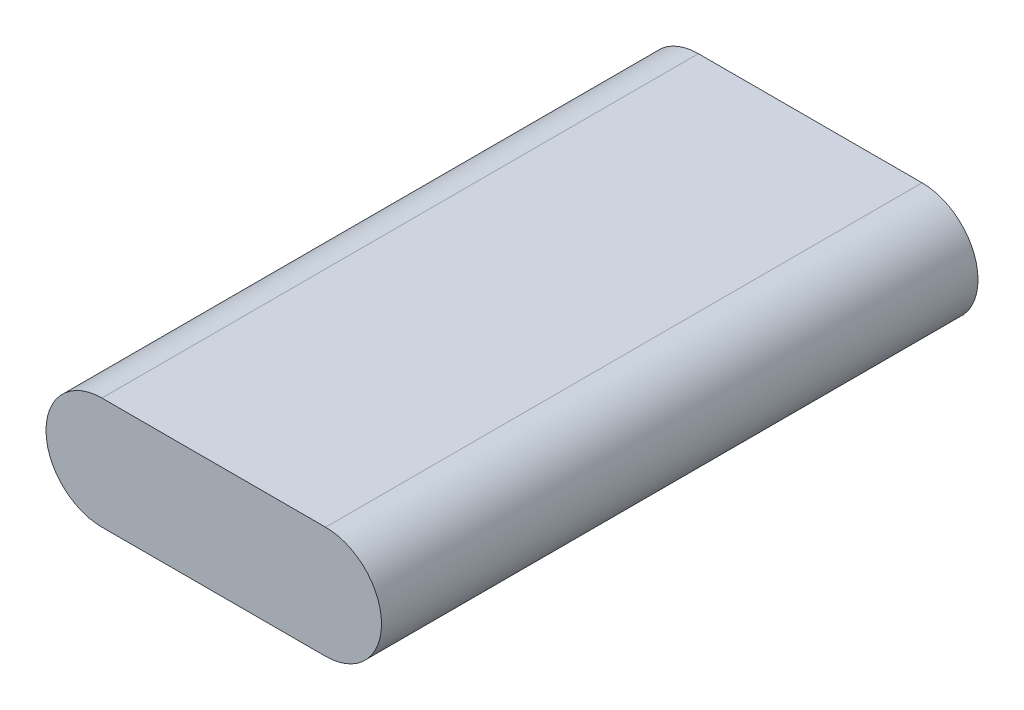
SolidWorks part; units mm, degrees
ref_plane "Front Plane" through (0, 0, 0) normal (0, 0, 1) x (1, 0, 0)
ref_plane "Top Plane" through (0, 0, 0) normal (0, 1, 0) x (1, 0, 0)
ref_plane "Right Plane" through (0, 0, 0) normal (1, 0, 0) x (0, 0, -1)
sketch "Sketch1" plane through (0, 0, 0) normal (0, 0, 1) x (1, 0, 0)
  line L0 (0, 0) -> (30, 0) construction
  line L1 (0, 7.5) -> (30, 7.5)
  line L2 (0, -7.5) -> (30, -7.5)
  arc A0 (0, 7.5) -> (0, -7.5) centre (0, 0) ccw
  arc A1 (30, -7.5) -> (30, 7.5) centre (30, 0) ccw
  point P3 (15, 0)
  dimension "D2" = 7.5
  dimension "D1" = 30
extrude "Boss-Extrude1" add sketch "Sketch1" along normal blind 80
